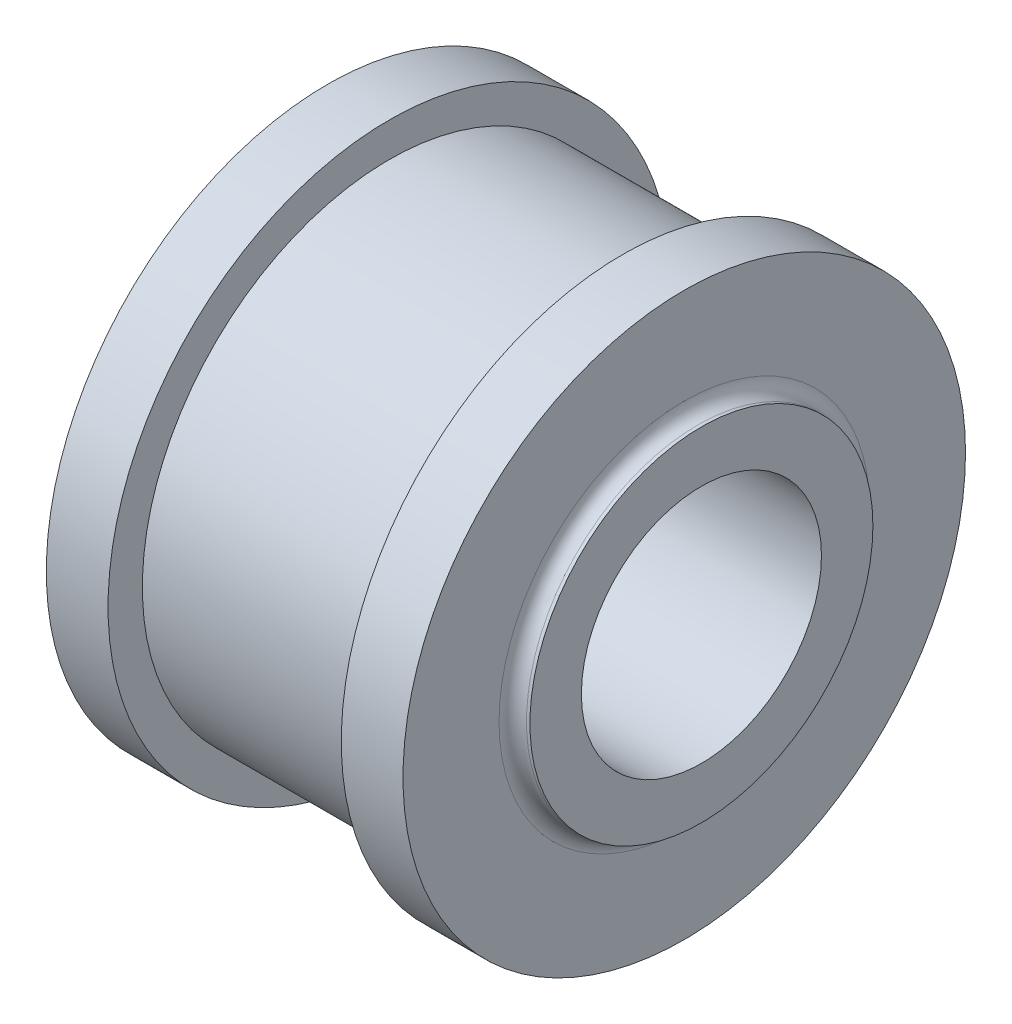
SolidWorks part; units mm, degrees
ref_plane "Front Plane" through (0, 0, 0) normal (0, 0, 1) x (1, 0, 0)
ref_plane "Top Plane" through (0, 0, 0) normal (0, 1, 0) x (1, 0, 0)
ref_plane "Right Plane" through (0, 0, 0) normal (1, 0, 0) x (0, 0, -1)
sketch "Sketch1" plane through (0, 0, 0) normal (0, 0, 1) x (1, 0, 0)
  line L0 (27.5209, -33.6102) -> (-10.127, -33.6102) construction
  line L1 (28.229, -16.1102) -> (28.229, -8.6102)
  line L2 (28.229, -8.6102) -> (25.729, -8.6102)
  line L3 (25.729, -8.6102) -> (25.729, 7.3898)
  line L4 (25.729, 7.3898) -> (16.729, 7.3898)
  line L5 (16.729, 7.3898) -> (16.729, 2.3898)
  line L6 (16.729, 2.3898) -> (-17.271, 2.3898)
  line L7 (-17.271, 2.3898) -> (-17.271, 7.3898)
  line L8 (-17.271, 7.3898) -> (-26.271, 7.3898)
  line L9 (-26.271, 7.3898) -> (-26.271, -8.6102)
  line L10 (-26.271, -8.6102) -> (-28.771, -8.6102)
  line L11 (-28.771, -8.6102) -> (-28.771, -16.1102)
  line L12 (-28.771, -16.1102) -> (28.229, -16.1102)
  line L13 (-0.271, -29.1016) -> (-0.271, 33.8812) construction
  point P16 (-0.271, 2.3898)
  dimension "D1" = 34
  dimension "D2" = 26
  dimension "D3" = 26
  dimension "D4" = 28.5
  dimension "D5" = 28.5
  dimension "D6" = 17.5
  dimension "D7" = 25
  dimension "D8" = 41
  dimension "D9" = 36
revolve "Revolve1" add sketch "Sketch1" angle 360 about L0
fillet "Fillet1" radius 2 2 edges at (25.729, -33.6102, -25) (-26.271, -33.6102, -25)
